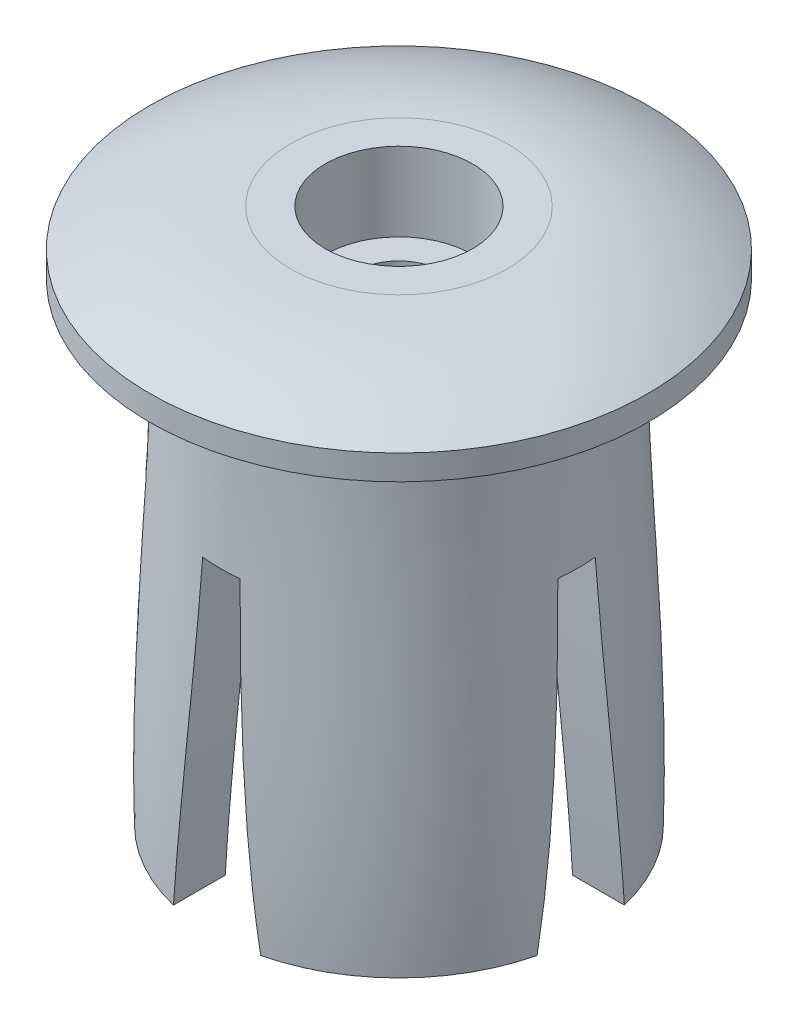
SolidWorks part; units mm, degrees
ref_plane "Front Plane" through (0, 0, 0) normal (0, 0, 1) x (1, 0, 0)
ref_plane "Top Plane" through (0, 0, 0) normal (0, 1, 0) x (1, 0, 0)
ref_plane "Right Plane" through (0, 0, 0) normal (1, 0, 0) x (0, 0, -1)
sketch "Sketch1" plane through (0, 0, 0) normal (0, 0, 1) x (1, 0, 0)
  line L0 (0, 61.7674) -> (0, 23.7229) construction
  line L1 (0, 23.7229) -> (5.5245, 23.7229)
  line L2 (8.89, 20.5479) -> (12.7, 20.5479)
  line L3 (12.7, 20.5479) -> (12.7, 21.8179)
  line L4 (0, -3.5821) -> (9.525, -3.5821)
  line L6 (0, 23.7229) -> (0, -3.5821)
  line L7 (0, -3.5821) -> (0, -56.4086) construction
  arc A0 (5.5245, 23.7229) -> (12.7, 21.8179) centre (5.5245, 9.2565) cw
  spline S0 degree 3 poles (8.89, 20.5479) (8.8496, 12.4979) (9.7412, 4.4692) (9.525, -3.5821) knots 0 0 0 0 1 1 1 1
  dimension "D1" = 5.5245
  dimension "D2" = 12.7
  dimension "D3" = 3.175
  dimension "D4" = 1.27
  dimension "D5" = 9.525
  dimension "D6" = 24.13
revolve "Revolve1" add sketch "Sketch1" angle 360 about L6
shell "Shell1" thickness 2.54
sketch3d "3DSketch3" plane through (0, 0, 0) normal (0, 0, 1) x (1, 0, 0)
  dimension "D1" = 12.7
sketch "Sketch4" plane through (0, 0, 12.7) normal (0, 0, 1) x (1, 0, 0)
  line L0 (0.9525, 12.2929) -> (-0.9525, 12.2929)
  line L1 (-9.525, -3.5821) -> (9.525, -3.5821) construction
  line L2 (2.2225, -3.5821) -> (-2.2225, -3.5821)
  spline S0 degree 2 poles (0.9525, 12.2929) (1.2666, 4.3273) (2.2225, -3.5821) knots 0 0 0 1 1 1
  spline S1 degree 2 poles (-0.9525, 12.2929) (-1.2666, 4.3273) (-2.2225, -3.5821) knots 0 0 0 1 1 1
extrude "Cut-Extrude2" cut sketch "Sketch4" against normal through all
pattern_circular "CirPattern1" count 2 every 90 of "Cut-Extrude2"
sketch "Sketch13" plane through (0, 20.5479, 0) normal (0, -1, 0) x (1, 0, 0)
  circle A1 centre (0, 0) radius 8.6639
extrude "Boss-Extrude3" add sketch "Sketch13" against normal blind 2.54 and the other way blind 6.985
hole_wizard "CBORE for M5 Hex Head Bolt2" positions "Sketch15" profile "Sketch14" counterbore size "M5" standard "Ansi Metric" end condition through all
sketch "Sketch15" plane through (0, 23.7229, 0) normal (0, 1, 0) x (-1, 0, 0)
  point P0 (0, 0)
  dimension "D1" = 0
sketch "Sketch14" plane through (0, 23.7229, 0) normal (1, 0, 0) x (0, 0, 1)
  line L0 (0, 0) -> (0, 27.305)
  line L1 (0, 27.305) -> (2.25, 27.305)
  line L3 (2.25, 27.305) -> (2.25, 4)
  line L4 (2.25, 4) -> (3.75, 4)
  line L5 (3.75, 4) -> (3.75, 0)
  line L7 (3.75, 0) -> (0, 0)
  line L11 (0, -6.35) -> (0, 107.95) construction
  dimension "Thru Hole Dia." = 4.5
  dimension "Thru Hole Depth" = 27.305
  dimension "C'Bore Dia." = 7.5
  dimension "C'Bore Depth" = 4
